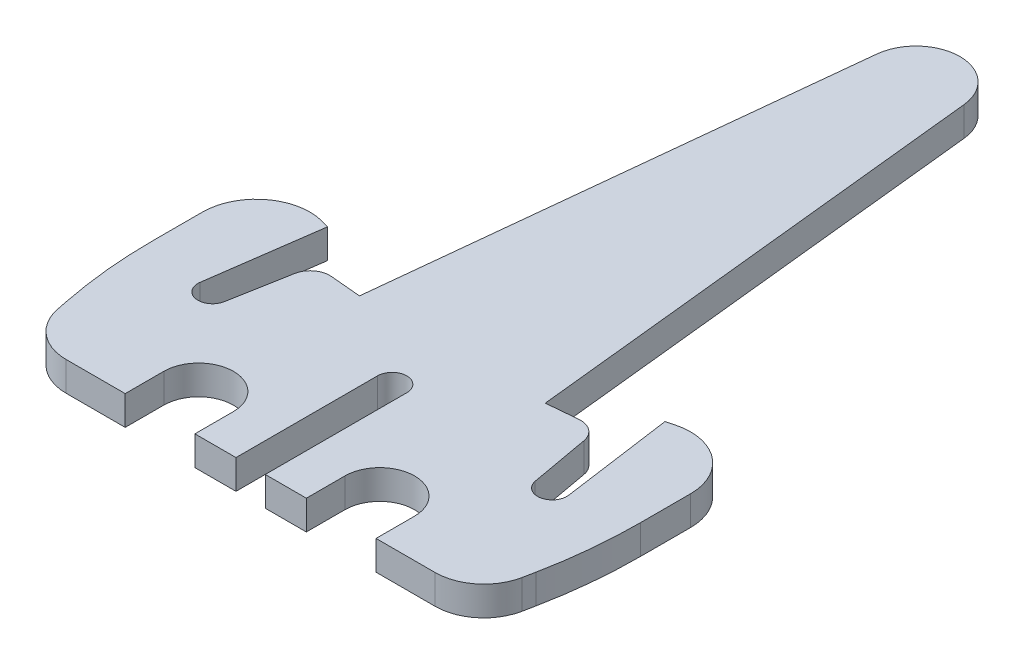
SolidWorks part; units mm, degrees
ref_plane "Front Plane" through (0, 0, 0) normal (0, 0, 1) x (1, 0, 0)
ref_plane "Top Plane" through (0, 0, 0) normal (0, 1, 0) x (1, 0, 0)
ref_plane "Right Plane" through (0, 0, 0) normal (1, 0, 0) x (0, 0, -1)
sketch "Sketch1" plane through (0, 0, 0) normal (0, 1, 0) x (1, 0, 0)
  line L0 (4.4753, 54.1404) -> (9.5172, 6.17)
  line L1 (9.5172, 6.17) -> (12.6814, 6.4563)
  line L4 (17.2833, 10.6723) -> (18.0765, 10.8849)
  line L5 (25, -14.5) -> (25, 5.5723)
  line L6 (25, -14.5) -> (12.85, -14.5) construction
  line L7 (12.85, -14.5) -> (12.85, -10.55)
  line L8 (5.71, -10.55) -> (5.71, -14.5)
  line L9 (5.71, -14.5) -> (1.5, -14.5)
  line L10 (1.5, -14.5) -> (1.5, 0)
  line L11 (-1.5, 0) -> (-1.5, -14.5)
  line L12 (-1.5, -14.5) -> (-5.71, -14.5)
  line L13 (-5.71, -14.5) -> (-5.71, -10.55)
  line L14 (-12.85, -10.55) -> (-12.85, -14.5)
  line L15 (-12.85, -14.5) -> (-25, -14.5) construction
  line L16 (-25, -14.5) -> (-25, 5.5723) construction
  line L17 (-18.0765, 10.8849) -> (-17.2833, 10.6723)
  line L21 (-9.5172, 6.17) -> (-4.4753, 54.1404)
  line L22 (0, 0) -> (0, 53.67) construction
  line L23 (-24.0358, -9.3022) -> (-23.8017, -10.4772)
  line L24 (24.0358, -9.3022) -> (23.8017, -10.4772)
  line L25 (-25, 5.5723) -> (-25, 0.4696)
  line L26 (25, 0.4696) -> (25, 5.5723)
  line L27 (-18.8981, -14.5) -> (-12.85, -14.5)
  line L28 (12.85, -14.5) -> (18.8981, -14.5)
  line L29 (17.2833, 10.6723) -> (18.8868, -0.7902)
  line L30 (15.925, -1.2638) -> (14.83, 4.8188)
  line L31 (17.4012, -0.998) -> (7.4753, 54.1404) construction
  line L32 (-17.2833, 10.6723) -> (-18.8868, -0.7902)
  line L33 (-15.925, -1.2638) -> (-14.83, 4.8188)
  line L34 (-9.5172, 6.17) -> (-12.6814, 6.4563)
  arc A0 (-4.4753, 54.1404) -> (4.4753, 54.1404) centre (0, 53.67) cw
  arc A1 (15.925, -1.2638) -> (18.8868, -0.7902) centre (17.4012, -0.998) ccw
  arc A2 (12.85, -10.55) -> (5.71, -10.55) centre (9.28, -10.55) ccw
  arc A3 (1.5, 0) -> (-1.5, 0) centre (0, 0) ccw
  arc A4 (-5.71, -10.55) -> (-12.85, -10.55) centre (-9.28, -10.55) ccw
  arc A6 (18.0765, 10.8849) -> (25, 5.5723) centre (19.5, 5.5723) cw
  arc A7 (-25, 5.5723) -> (-18.0765, 10.8849) centre (-19.5, 5.5723) cw
  arc A8 (23.8017, -10.4772) -> (18.8981, -14.5) centre (18.8981, -9.5) cw
  arc A9 (-23.8017, -10.4772) -> (-18.8981, -14.5) centre (-18.8981, -9.5) ccw
  arc A10 (24.0358, -9.3022) -> (25, 0.4696) centre (-25, 0.4696) ccw
  arc A11 (-24.0358, -9.3022) -> (-25, 0.4696) centre (25, 0.4696) cw
  arc A14 (12.6814, 6.4563) -> (14.83, 4.8188) centre (12.8616, 4.4644) cw
  arc A15 (-15.925, -1.2638) -> (-18.8868, -0.7902) centre (-17.4012, -0.998) cw
  arc A16 (-12.6814, 6.4563) -> (-14.83, 4.8188) centre (-12.8616, 4.4644) ccw
  point P15 (7.4753, 54.1404)
  point P32 (0, 58.17)
  point P33 (-14.139, 6.4563)
  point P35 (0, 1.5)
  point P36 (9.28, -6.98)
  point P43 (23, -14.5)
  point P46 (-23, -14.5)
  point P52 (25, 12.74)
  point P56 (25, -4.4639)
  point P59 (-25, -4.4639)
  point P61 (9.5172, 6.17)
  point P62 (-12.2739, 6.4563)
  point P63 (0, 0)
  point P66 (0, 0)
  point P67 (17.4029, -0.9502)
  point P68 (9.2919, 6.17)
  point P69 (25.0119, 5.5723)
  point P72 (4.4753, 54.1404)
  point P73 (-4.4753, 53.67)
  point P74 (0, 54.1404)
  point P75 (-9.2716, 6.5134)
  point P76 (0, 0)
  point P77 (0, 0)
  point P78 (0, 0)
  point P79 (13.3841, 2.5336)
  point P80 (14.6812, 4.8188)
  point P81 (15.9262, -1.2638)
  point P82 (18.8897, -0.9518)
  point P83 (17.4024, 10.8849)
  point P84 (18.0849, 10.6723)
  point P85 (25.0084, 5.5723)
  point P86 (23.7933, -9.5)
  point P87 (24.0357, -10.55)
  point P88 (18.8897, -14.5)
  point P89 (0, 0)
  point P90 (34.4916, 6.5133)
  point P92 (0, 0)
  point P93 (0, 0)
  point P94 (-17.4012, 10.8849)
  point P95 (1.5, 0)
  point P96 (0, 0)
  point P97 (1.5, 0)
  point P98 (1.5, 0)
  dimension "D1" = 4.5
  dimension "D6" = 1.5
  dimension "D8" = 3.57
  dimension "D14" = 72.67
  dimension "D12" = 10.6723
  dimension "D15" = 5.5
  dimension "D17" = 5
  dimension "D18" = 50
  dimension "D19" = 2
  dimension "D23" = 19.3188
  dimension "D11" = 6.5703
  dimension "D2" = 12
  dimension "D3" = 17.2833
  dimension "D4" = 72.67
  dimension "D5" = 50
  dimension "D7" = 16
  dimension "D9" = 7.52
  dimension "11.42" = 11.42
  dimension "D10" = 52
  dimension "D13" = 81
  dimension "45.43" = 45.43
  dimension "D16" = 2
  dimension "D20" = 15.9012
  dimension "D21" = 3
  dimension "D22" = 13.502
  dimension "D24" = 18.8981
extrude "Boss-Extrude1" add sketch "Sketch1" along normal blind 3
